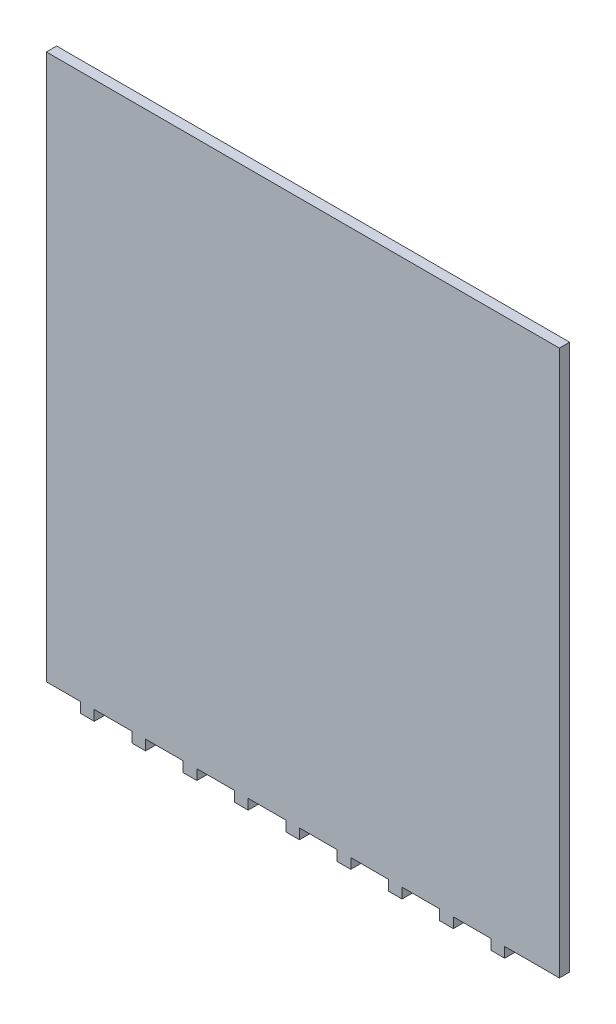
SolidWorks part; units mm, degrees
ref_plane "Front Plane" through (0, 0, 0) normal (0, 0, 1) x (1, 0, 0)
ref_plane "Top Plane" through (0, 0, 0) normal (0, 1, 0) x (1, 0, 0)
ref_plane "Right Plane" through (0, 0, 0) normal (1, 0, 0) x (0, 0, -1)
sketch "Sketch1" plane through (0, 0, 0) normal (0, 0, 1) x (1, 0, 0)
  line L1 (0, 0) -> (300, 0)
  line L2 (0, 0) -> (0, -325)
  line L3 (0, -325) -> (300, -325)
  line L4 (300, 0) -> (300, -325)
  dimension "D1" = 325
  dimension "D2" = 300
extrude "Boss-Extrude1" add sketch "Sketch1" along normal blind 6
sketch "Sketch2" plane through (0, 0, 6) normal (0, 0, 1) x (1, 0, 0)
  line L0 (0, 0) -> (0, -325) construction
  line L1 (20, -319) -> (28, -319) construction
  line L2 (0, -325) -> (300, -325) construction
  line L3 (28, -319) -> (50, -319)
  line L4 (20, -325) -> (20, -319)
  line L5 (28, -319) -> (28, -325)
  line L6 (28, -325) -> (50, -325)
  line L7 (50, -319) -> (50, -325)
  line L8 (20, -319) -> (0, -319)
  line L9 (0, -319) -> (0, -325)
  line L10 (0, -325) -> (20, -325)
  line L11 (58, -319) -> (58, -325)
  line L12 (58, -319) -> (80, -319)
  line L13 (58, -325) -> (80, -325)
  line L14 (80, -319) -> (80, -325)
  line L15 (88, -319) -> (88, -325)
  line L16 (88, -319) -> (110, -319)
  line L17 (88, -325) -> (110, -325)
  line L18 (110, -319) -> (110, -325)
  line L19 (118, -319) -> (118, -325)
  line L20 (118, -319) -> (140, -319)
  line L21 (118, -325) -> (140, -325)
  line L22 (140, -319) -> (140, -325)
  line L23 (148, -319) -> (148, -325)
  line L24 (148, -319) -> (170, -319)
  line L25 (148, -325) -> (170, -325)
  line L26 (170, -319) -> (170, -325)
  line L27 (178, -319) -> (178, -325)
  line L28 (178, -319) -> (200, -319)
  line L29 (178, -325) -> (200, -325)
  line L30 (200, -319) -> (200, -325)
  line L31 (208, -319) -> (208, -325)
  line L32 (208, -319) -> (230, -319)
  line L33 (208, -325) -> (230, -325)
  line L34 (230, -319) -> (230, -325)
  line L35 (238, -319) -> (238, -325)
  line L36 (238, -319) -> (260, -319)
  line L37 (238, -325) -> (260, -325)
  line L38 (260, -319) -> (260, -325)
  line L39 (268, -319) -> (268, -325)
  line L40 (268, -319) -> (300, -319)
  line L41 (268, -325) -> (300, -325)
  line L42 (300, -325) -> (300, -319)
  line L44 (300, -325) -> (300, 0) construction
  line L46 (290, -319) -> (290, -325) [skipped]
  line L49 (268, -319) -> (290, -319) [skipped]
  line L50 (268, -325) -> (290, -325) [skipped]
  point P0 (20, -322)
  dimension "D1" = 20
  dimension "D2" = 6
  dimension "D3" = 8
  dimension "D4" = 22
  dimension "D5" = 9
extrude "Cut-Extrude1" cut sketch "Sketch2" against normal through all
